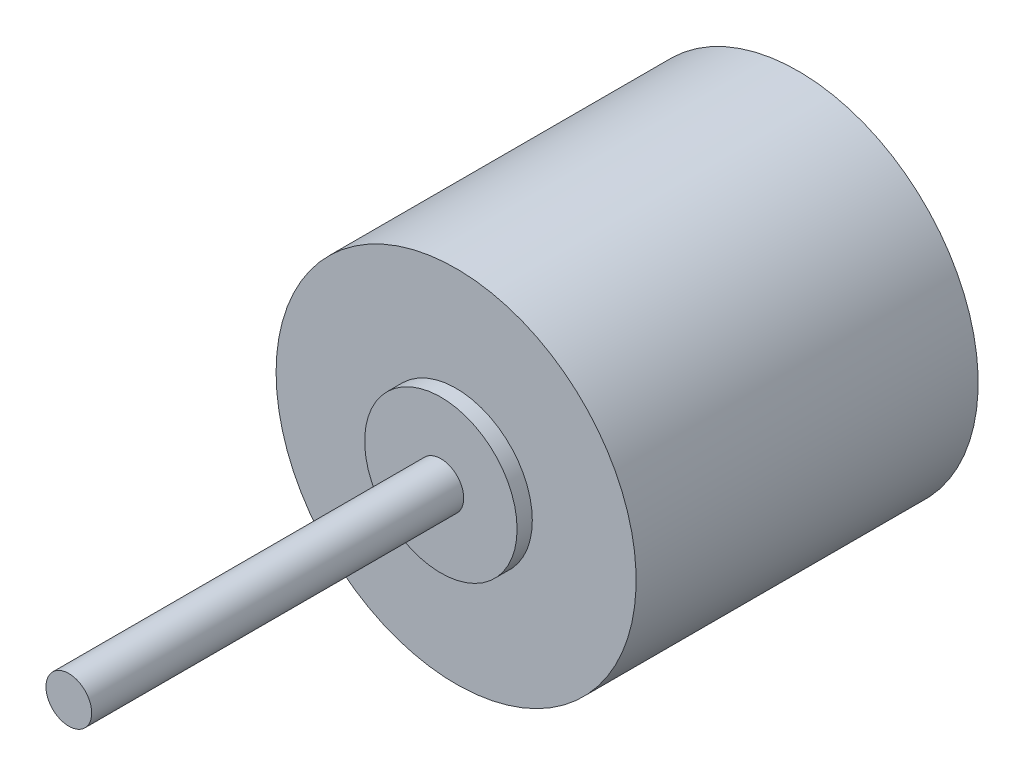
SolidWorks part; units mm, degrees
material "1060 Alloy"
ref_plane "Front" through (0, 0, 0) normal (0, 0, 1) x (1, 0, 0)
ref_plane "Top" through (0, 0, 0) normal (0, 1, 0) x (1, 0, 0)
ref_plane "Right" through (0, 0, 0) normal (1, 0, 0) x (0, 0, -1)
sketch "Sketch1" plane through (0, 0, 0) normal (0, 0, 1) x (1, 0, 0)
  circle A0 centre (0, 0) radius 30
  dimension "D1" = 60
extrude "Boss-Extrude1" add sketch "Sketch1" along normal blind 57 contours A0
sketch "Sketch2" plane through (0, 0, 57) normal (0, 0, 1) x (1, 0, 0)
  circle A0 centre (0, 0) radius 12.7
  dimension "D1" = 25.4
extrude "Boss-Extrude2" add sketch "Sketch2" along normal blind 2.54
sketch "Sketch3" plane through (0, 0, 59.54) normal (0, 0, 1) x (1, 0, 0)
  circle A0 centre (0, 0) radius 3.81
  dimension "D1" = 7.62
extrude "Boss-Extrude3" add sketch "Sketch3" along normal blind 62
sketch "Sketch4" plane through (0, 0, 0) normal (0, 0, -1) x (-1, 0, 0)
  circle A0 centre (0, 0) radius 16
  circle A1 centre (0, -16) radius 2
  circle A2 centre (-16, 0) radius 2
  circle A3 centre (0, 16) radius 2
  circle A4 centre (16, 0) radius 2
  dimension "D1" = 32
  dimension "D2" = 4
  dimension "D3" = 4
extrude "Cut-Extrude1" cut sketch "Sketch4" against normal blind 5.08 contours A4 | A3 | A2 | A1
